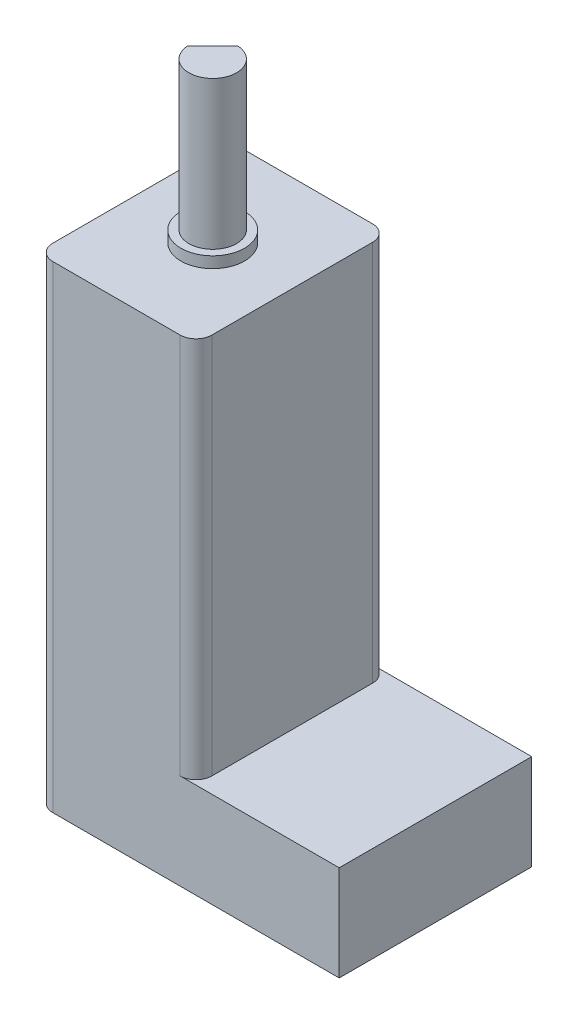
SolidWorks part; units mm, degrees
ref_plane "前视基准面" through (0, 0, 0) normal (0, 0, 1) x (1, 0, 0)
ref_plane "上视基准面" through (0, 0, 0) normal (0, 1, 0) x (1, 0, 0)
ref_plane "右视基准面" through (0, 0, 0) normal (1, 0, 0) x (0, 0, -1)
other "Configuration Table"
sketch "Sketch1" plane through (0, 0, 0) normal (0, 1, 0) x (1, 0, 0)
  line L1 (-5, 6.05) -> (5, 6.05)
  line L2 (-5, 6.05) -> (-5, -6.05)
  line L3 (-5, -6.05) -> (5, -6.05)
  line L4 (5, 6.05) -> (5, -6.05)
  line L5 (-5, 6.05) -> (5, -6.05) construction
  line L6 (-5, -6.05) -> (5, 6.05) construction
  point P0 (0, 0)
  dimension "D1" = 12.1
  dimension "D2" = 10
extrude "Boss-Extrude1" add sketch "Sketch1" along normal blind 30
sketch "Sketch2" plane through (0, 30, 0) normal (0, 1, 0) x (1, 0, 0)
  circle A0 centre (0, 0) radius 2
extrude "Boss-Extrude2" add sketch "Sketch2" along normal blind 0.7
sketch "Sketch3" plane through (0, 30.7, 0) normal (0, 1, 0) x (1, 0, 0)
  line L0 (0.0835, 1.4977) -> (-1.4977, -0.0835)
  circle A0 centre (0, 0) radius 1.5
  dimension "D1" = 1
extrude "Boss-Extrude3" add sketch "Sketch3" along normal blind 9.3 contours L0 A0
fillet "Fillet1" radius 1 4 edges at (5, 15, -6.05) (-5, 15, -6.05) (-5, 15, 6.05) (5, 15, 6.05)
sketch "Sketch4" plane through (0, 0, 0) normal (1, 0, 0) x (0, 0, -1)
  line L5 (-6.05, 0) -> (-6.05, 30) construction
  line L6 (-6.05, 6) -> (6.05, 6)
  line L7 (-6.05, 6) -> (-6.05, 0)
  line L8 (-6.05, 0) -> (6.05, 0)
  line L9 (6.05, 6) -> (6.05, 0)
  line L10 (6.05, 30) -> (6.05, 0) construction
  line L11 (-5.05, 30) -> (5.05, 30) construction
  line L12 (-5.05, 0) -> (5.05, 0) construction
  dimension "D1" = 24
extrude "Boss-Extrude4" add sketch "Sketch4" along normal blind 14
